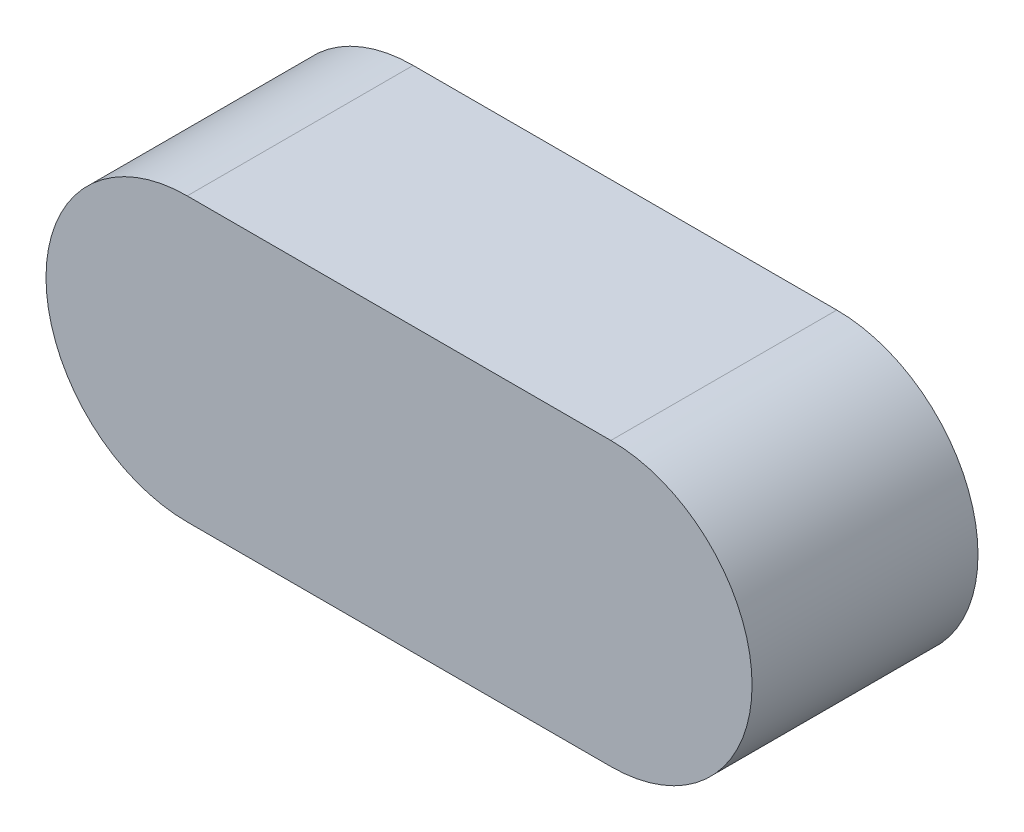
SolidWorks part; units mm, degrees
ref_plane "Piano frontale" through (0, 0, 0) normal (0, 0, 1) x (1, 0, 0)
ref_plane "Piano superiore" through (0, 0, 0) normal (0, 1, 0) x (1, 0, 0)
ref_plane "Piano destro" through (0, 0, 0) normal (1, 0, 0) x (0, 0, -1)
sketch "Schizzo1" plane through (0, 0, 0) normal (0, 0, 1) x (1, 0, 0)
  line L0 (9.5993, 0) -> (24.5993, 0) construction
  line L1 (9.5993, 5) -> (24.5993, 5)
  line L2 (9.5993, -5) -> (24.5993, -5)
  arc A0 (9.5993, 5) -> (9.5993, -5) centre (9.5993, 0) ccw
  arc A1 (24.5993, -5) -> (24.5993, 5) centre (24.5993, 0) ccw
  point P3 (17.0993, 0)
  dimension "D1" = 15
  dimension "D2" = 10
extrude "Estrusione-Estrusione1" add sketch "Schizzo1" along normal blind 8
